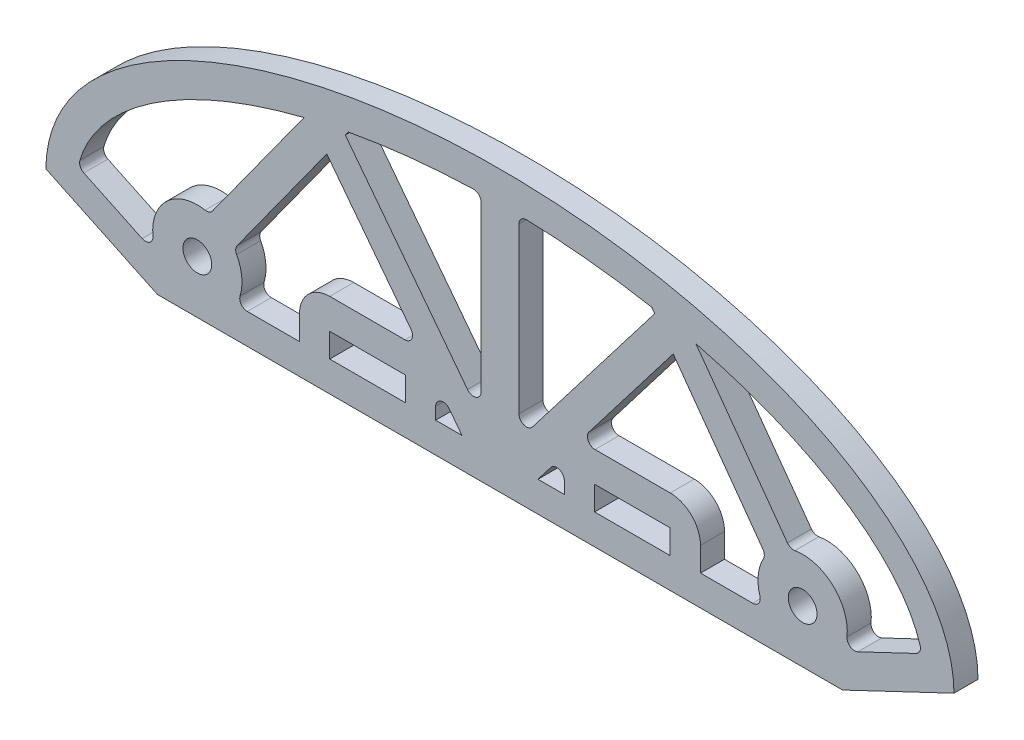
SolidWorks part; units mm, degrees
material "Birch Plywood"
ref_plane "Front Plane" through (0, 0, 0) normal (0, 0, 1) x (1, 0, 0)
ref_plane "Top Plane" through (0, 0, 0) normal (0, 1, 0) x (1, 0, 0)
ref_plane "Right Plane" through (0, 0, 0) normal (1, 0, 0) x (0, 0, -1)
sketch "Sketch3" plane through (0, 0, 0) normal (0, 0, 1) x (1, 0, 0)
  line L0 (85.2659, 27.2) -> (74.7341, 27.2) construction
  line L1 (74.7341, 27.2) -> (74.7341, 15.2) construction
  line L2 (74.7341, 15.2) -> (85.2659, 15.2) construction
  line L3 (85.2659, 15.2) -> (85.2659, 27.2) construction
  line L4 (5.2659, 27.2) -> (-5.2659, 27.2) construction
  line L5 (-5.2659, 27.2) -> (-5.2659, 15.2) construction
  line L6 (-5.2659, 15.2) -> (5.2659, 15.2) construction
  line L7 (5.2659, 15.2) -> (5.2659, 27.2) construction
  line L8 (85.2659, 27.2) -> (74.7341, 27.2) construction
  line L9 (74.7341, 27.2) -> (74.7341, 15.2) construction
  line L10 (74.7341, 15.2) -> (85.2659, 15.2) construction
  line L11 (85.2659, 15.2) -> (85.2659, 27.2) construction
  line L12 (5.2659, 27.2) -> (-5.2659, 27.2) construction
  line L13 (-5.2659, 27.2) -> (-5.2659, 15.2) construction
  line L14 (-5.2659, 15.2) -> (5.2659, 15.2) construction
  line L15 (5.2659, 15.2) -> (5.2659, 27.2) construction
  line L16 (0, 22.2) -> (80, 22.2) construction
  line L17 (-20, 22.2) -> (0, 22.2) construction
  line L18 (80, 22.2) -> (100, 22.2) construction
  line L19 (-20, 22.2) -> (-20, 52.2) construction
  line L20 (-20, 52.2) -> (40, 52.2) construction
  line L21 (-20, 22.2) -> (-5.2659, 15.2)
  line L22 (-5.2659, 15.2) -> (85.2659, 15.2)
  line L23 (85.2659, 15.2) -> (100, 22.2)
  line L24 (40, 52.2) -> (40, 15.2) construction
  line L25 (52.5, 22.375) -> (52.5, 19.2)
  line L26 (17.5, 22.375) -> (27.5, 22.375)
  line L27 (17.5, 22.375) -> (17.5, 19.2)
  line L28 (17.5, 19.2) -> (27.5, 19.2)
  line L29 (27.5, 22.375) -> (27.5, 19.2)
  line L30 (62.5, 19.2) -> (52.5, 19.2)
  line L31 (62.5, 22.375) -> (62.5, 19.2)
  line L32 (62.5, 22.375) -> (52.5, 22.375)
  circle A0 centre (80, 22.2) radius 1.9 construction
  circle A1 centre (0, 22.2) radius 1.9 construction
  circle A2 centre (80, 22.2) radius 1.9
  circle A3 centre (0, 22.2) radius 1.9
  ellipse E0 centre (40, 22.2) end of major axis (100, 22.2) minor radius 30 (100, 22.2) -> (-20, 22.2) ccw
  dimension "D1" = 30
  dimension "D2" = 60
  dimension "D3" = 10
  dimension "D4" = 3.175
  dimension "D5" = 4
  dimension "D6" = 25
extrude "Boss-Extrude1" add sketch "Sketch3" along normal blind 3.175
sketch "Sketch4" plane through (0, 0, 3.175) normal (0, 0, 1) x (1, 0, 0)
  line L0 (-15.7375, 24.6034) -> (-5.3232, 19.6557)
  line L1 (5.0804, 19.2) -> (74.9196, 19.2)
  line L2 (85.3232, 19.6557) -> (95.7375, 24.6034)
  line L3 (85.2659, 15.2) -> (100, 22.2)
  line L4 (52.5, 22.375) -> (52.5, 19.2)
  line L5 (62.5, 22.375) -> (52.5, 22.375)
  line L6 (62.5, 19.2) -> (62.5, 22.375)
  line L7 (52.5, 19.2) -> (62.5, 19.2)
  line L8 (52.5, 22.375) -> (52.5, 19.2) construction
  line L9 (62.5, 22.375) -> (52.5, 22.375) construction
  line L10 (62.5, 19.2) -> (62.5, 22.375) construction
  line L11 (52.5, 19.2) -> (62.5, 19.2) construction
  line L12 (17.5, 19.2) -> (27.5, 19.2)
  line L13 (17.5, 22.375) -> (17.5, 19.2)
  line L14 (27.5, 22.375) -> (17.5, 22.375)
  line L15 (27.5, 19.2) -> (27.5, 22.375)
  line L16 (17.5, 19.2) -> (27.5, 19.2) construction
  line L17 (17.5, 22.375) -> (17.5, 19.2) construction
  line L18 (27.5, 22.375) -> (17.5, 22.375) construction
  line L19 (27.5, 19.2) -> (27.5, 22.375) construction
  line L20 (-20, 22.2) -> (-5.2659, 15.2)
  line L21 (-5.2659, 15.2) -> (85.2659, 15.2)
  line L22 (85.2659, 15.2) -> (100, 22.2) construction
  line L23 (-20, 22.2) -> (-5.2659, 15.2) construction
  line L24 (-5.2659, 15.2) -> (85.2659, 15.2) construction
  line L25 (17.5, 26.375) -> (27.5, 26.375)
  line L26 (13.5, 22.375) -> (13.5, 19.2)
  line L27 (31.5, 22.375) -> (31.5, 19.2)
  line L28 (40, 15.2) -> (40, 52.2) construction
  line L29 (48.5, 22.375) -> (48.5, 19.2)
  line L30 (62.5, 26.375) -> (52.5, 26.375)
  line L31 (66.5, 22.375) -> (66.5, 19.2)
  line L32 (-4.364, 19.2) -> (84.364, 19.2) construction
  line L33 (-15.7375, 24.6034) -> (-4.364, 19.2) construction
  line L34 (84.364, 19.2) -> (95.7375, 24.6034) construction
  line L35 (37.5, 48.2) -> (42.5, 48.2)
  line L36 (37.5, 48.2) -> (37.5, 19.2)
  line L37 (37.5, 19.2) -> (42.5, 19.2)
  line L38 (42.5, 48.2) -> (42.5, 19.2)
  line L39 (17.0606, 45.8325) -> (37.5, 19.2) construction
  line L40 (14.9152, 45.3431) -> (34.9789, 19.2)
  line L41 (37.5, 22.485) -> (19.2406, 46.277)
  line L42 (24.947, 32.2715) -> (28.1202, 34.7068) construction
  line L43 (0, 22.2) -> (17.0606, 45.8325) construction
  line L44 (14.0952, 45.1417) -> (1.6274, 27.8711)
  line L45 (4.8705, 25.5298) -> (19.5537, 45.8691)
  line L46 (7.8613, 36.5064) -> (11.1045, 34.1651) construction
  line L47 (42.5, 19.2) -> (62.9394, 45.8325) construction
  line L48 (62.9394, 45.8325) -> (80, 22.2) construction
  line L49 (60.7594, 46.277) -> (42.5, 22.485)
  line L50 (45.0211, 19.2) -> (65.0848, 45.3431)
  line L51 (75.1295, 25.5298) -> (60.0562, 46.4094)
  line L52 (78.3726, 27.8711) -> (65.9048, 45.1417)
  line L53 (51.6297, 34.381) -> (54.8029, 31.9457) construction
  line L54 (72.1387, 36.5064) -> (68.8955, 34.1651) construction
  line L55 (19.5537, 45.8691) -> (19.9438, 46.4094)
  arc A0 (85.3232, 19.6557) -> (74.9196, 19.2) centre (80, 22.2) ccw
  circle A1 centre (80, 22.2) radius 1.9
  circle A2 centre (80, 22.2) radius 1.9 construction
  circle A3 centre (0, 22.2) radius 1.9
  circle A4 centre (0, 22.2) radius 1.9 construction
  arc A5 (5.0804, 19.2) -> (-5.3232, 19.6557) centre (0, 22.2) ccw
  circle A7 centre (0, 22.2) radius 5.9 construction
  circle A8 centre (80, 22.2) radius 5.9 construction
  arc A10 (17.5, 26.375) -> (13.5, 22.375) centre (17.5, 22.375) ccw
  arc A11 (31.5, 22.375) -> (27.5, 26.375) centre (27.5, 22.375) ccw
  arc A12 (48.5, 22.375) -> (52.5, 26.375) centre (52.5, 22.375) cw
  arc A13 (62.5, 26.375) -> (66.5, 22.375) centre (62.5, 22.375) cw
  arc A14 (28.2377, 27.9838) -> (27.4444, 26.375) centre (27.4444, 27.375) cw
  arc A15 (33.2933, 21.3963) -> (31.5, 20.7875) centre (32.5, 20.7875) ccw
  arc A16 (48.5, 20.7875) -> (46.7067, 21.3963) centre (47.5, 20.7875) ccw
  arc A17 (52.5556, 26.375) -> (51.7623, 27.9838) centre (52.5556, 27.375) cw
  ellipse E1 centre (40, 22.2) end of major axis (100, 22.2) minor radius 30 (100, 22.2) -> (-20, 22.2) ccw
  ellipse E2 centre (40, 22.2) end of major axis (100, 22.2) minor radius 30 (100, 22.2) -> (-20, 22.2) ccw construction
  spline S0 degree 1 poles (95.7375, 24.6034) (-15.7375, 24.6034) knots 0 0 1 1 construction
  spline S1 degree 3 poles (95.7375, 24.6034) (95.6622, 24.948) (95.4837, 25.6219) (94.9892, 27.0049) (94.1127, 28.758) (92.6161, 30.899) (90.0114, 33.7557) (85.6121, 37.2373) (78.6564, 40.9913) (71.8583, 43.5232) (67.3393, 44.7824) (65.7688, 45.1759) (65.4958, 45.2432) (65.2221, 45.3101) (64.7849, 45.4153) (64.1815, 45.5566) (63.356, 45.7431) (62.5185, 45.9239) (61.6693, 46.0987) (61.0635, 46.2186) (60.6425, 46.2994) (60.4083, 46.3438) (60.1738, 46.3877) (57.6339, 46.8566) (52.6559, 47.584) (44.2604, 48.2378) (35.7396, 48.2378) (27.3441, 47.584) (22.3661, 46.8566) (19.8262, 46.3877) (19.5917, 46.3438) (19.3575, 46.2994) (18.9365, 46.2186) (18.3307, 46.0987) (17.4815, 45.9239) (16.644, 45.7431) (15.8185, 45.5566) (15.2151, 45.4153) (14.7779, 45.3101) (14.5042, 45.2432) (14.2312, 45.1759) (12.6607, 44.7824) (8.1417, 43.5232) (1.3436, 40.9913) (-5.6121, 37.2373) (-10.0114, 33.7557) (-12.6161, 30.899) (-14.1127, 28.758) (-14.9892, 27.0049) (-15.4837, 25.6219) (-15.6622, 24.948) (-15.7375, 24.6034) knots 3.250373 3.250373 3.250373 3.250373 3.296061 3.341749 3.433125 3.524501 3.615877 3.798629 3.981381 4.164133 4.243947 4.251896 4.25587 4.259844 4.267792 4.281193 4.294593 4.31502 4.328713 4.342405 4.348917 4.352174 4.35543 4.361942 4.492953 4.623963 4.800815 4.931825 5.062836 5.069348 5.072604 5.075861 5.082373 5.096065 5.109758 5.130185 5.143585 5.156986 5.164934 5.168908 5.172882 5.180831 5.260645 5.443397 5.626149 5.808901 5.900277 5.991653 6.083029 6.128717 6.174405 6.174405 6.174405 6.174405
  point P42 (85.9, 22.2)
  point P43 (5.9, 22.2)
  point P53 (40, 19.2)
  point P54 (40, 48.2)
  point P68 (26.5336, 33.4892)
  point P75 (9.4829, 35.3358)
  point P79 (53.2163, 33.1633)
  point P82 (70.5171, 35.3358)
  dimension "D7" = 4
  dimension "D10" = 4
  dimension "D14" = 1
  dimension "D9" = 5
  dimension "D11" = 4
  dimension "D12" = 4
  dimension "D13" = 4
  dimension "D1" = 0
  dimension "D2" = 0
  dimension "D3" = 0
  dimension "D4" = 0
  dimension "D5" = 0
  dimension "D6" = 4
  dimension "D8" = 4
extrude "Cut-Extrude2" cut sketch "Sketch4" against normal up to surface (3.175 mm away) contours L44 S1 L0 A5 | A14 L40 L45 A5 L1 L26 A10 L25 | L36 S1 L55 L41 | L40 A15 L27 L1 | L51 S1 L38 L49 | L29 A16 L50 L1 | A17 L30 A13 L31 L1 A0 L51 L50 | L2 S1 L52 A0 up to face at (57.5, 20.7875, 0)
fillet "Fillet1" radius 1 14 edges at (95.7375, 24.6034, 1.5875) (-15.7375, 24.6034, 1.5875) (-5.3232, 19.6557, 1.5875) (5.0804, 19.2, 1.5875) (4.8705, 25.5298, 1.5875) (1.6274, 27.8711, 1.5875) (37.5, 22.485, 1.5875) (37.5, 48.173, 1.5875) (42.5, 48.173, 1.5875) (42.5, 22.485, 1.5875) (85.3232, 19.6557, 1.5875) (78.3726, 27.8711, 1.5875) (74.9196, 19.2, 1.5875) (75.1295, 25.5298, 1.5875)
equation "\"prop-dist\"= 80mm"
equation "\"prop-hole-depth\"= 9mm"
equation "\"prop-hole-diameter\"= 11mm"
equation "\"rivet-extension\"= 12mm"
equation "\"rivet-hole-extension\"= 7mm"
equation "\"rivet-hole-diameter\"= 3.8mm"
equation "\"ski-length\"= 100mm"
equation "\"th\"= 0.125in'material thickness"
equation "\"ski-height\"= 30mm"
equation "\"ski-curve-gap\"= 60mm"
equation "\"ski-curve-height\"= \"rivet-hole-extension\""
equation "\"min-width\"= 4mm"
equation "\"prop-hole-diameter-small\"= 8.6mm"
equation "\"prop-dist-width\"= 86.5mm"
equation "\"prop-dist-length\"= 80mm"
equation "\"prop-boost\"= 4.4mm"
equation "\"back-drop\"= 5mm"
equation "\"T\"= 0.125in'Material Thickness"
equation "\"tof_c2c\"= 19.9mm'Center to center distance of TOF sensor holes"
equation "\"tof_d\"= 3mm'TOF hole diameter"
equation "\"tof_w\"= 12.6mm'TOF width"
equation "\"tof_l\"= 15.6mm'TOF length"
equation "\"pin_w\"= 2.3mm'A standard IO Pin socket width"
equation "\"pin_l\"= 2.5mm'A standard IO Pin socket length"
equation "\"esp_pin_num\"= 8'Number of pins on one side of the ESP"
equation "\"esp_l\"= 40mm'ESP length"
equation "\"esp_w\"= 27mm'ESP width"
equation "\"esp_pin_inset\"= 3mm'Distance that ESP pins are inset"
equation "\"bat_l\"= 27mm'Battery length"
equation "\"bat_w\"= 20mm'Battery width"
equation "\"bat_h\"= 6mm'Battery thickness"
equation "\"boost_w\"= 17.2mm"
equation "\"boost_l\"= 37mm"
equation "\"boost_hole_inset\"= 2.2mm"
equation "\"boost_hole_dist\"= 7mm"
equation "\"boost_hole_d\"= 2mm"
equation "\"support_width\"= 10mm"
equation "\"support_gap\"= 25mm"
equation "\"D1@Sketch3\"=\"ski-height\""
equation "\"D2@Sketch3\"=\"ski-curve-gap\""
equation "\"D3@Sketch3\"=\"support_width\""
equation "\"D4@Sketch3\"=\"T\""
equation "\"D6@Sketch3\"=\"support_gap\""
equation "\"D1@Boss-Extrude1\"=\"T\""
